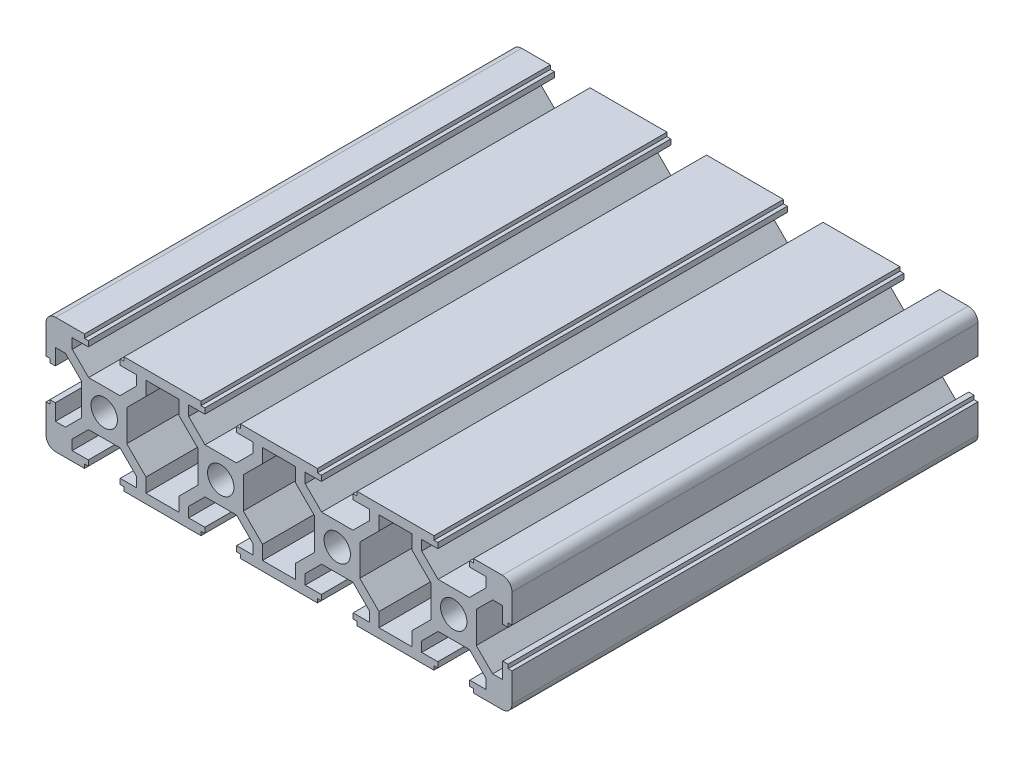
SolidWorks part; units mm, degrees
ref_plane "前视基准面" through (0, 0, 0) normal (0, 0, 1) x (1, 0, 0)
ref_plane "上视基准面" through (0, 0, 0) normal (0, 1, 0) x (1, 0, 0)
ref_plane "右视基准面" through (0, 0, 0) normal (1, 0, 0) x (0, 0, -1)
sketch "草图1" plane through (0, 0, 0) normal (0, 0, 1) x (1, 0, 0)
  line B0 (84.2, -4.0358) -> (84.2, 4.0358)
  line B1 (84.2, 4.0358) -> (79.25, 8.9858)
  line B2 (79.25, 8.9858) -> (79.25, 12.6)
  line B3 (79.25, 12.6) -> (70.75, 12.6)
  line B4 (70.75, 12.6) -> (70.75, 8.9858)
  line B5 (70.75, 8.9858) -> (65.8, 4.0358)
  line B6 (65.8, 4.0358) -> (65.8, -4.0358)
  line B7 (65.8, -4.0358) -> (70.75, -8.9858)
  line B8 (70.75, -8.9858) -> (70.75, -12.6)
  line B9 (70.75, -12.6) -> (79.25, -12.6)
  line B10 (79.25, -12.6) -> (79.25, -8.9858)
  line B11 (79.25, -8.9858) -> (84.2, -4.0358)
  line B12 (54.2, -4.0358) -> (54.2, 4.0358)
  line B13 (54.2, 4.0358) -> (49.25, 8.9858)
  line B14 (49.25, 8.9858) -> (49.25, 12.6)
  line B15 (49.25, 12.6) -> (40.75, 12.6)
  line B16 (40.75, 12.6) -> (40.75, 8.9858)
  line B17 (40.75, 8.9858) -> (35.8, 4.0358)
  line B18 (35.8, 4.0358) -> (35.8, -4.0358)
  line B19 (35.8, -4.0358) -> (40.75, -8.9858)
  line B20 (40.75, -8.9858) -> (40.75, -12.6)
  line B21 (40.75, -12.6) -> (49.25, -12.6)
  line B22 (49.25, -12.6) -> (49.25, -8.9858)
  line B23 (49.25, -8.9858) -> (54.2, -4.0358)
  line B24 (24.2, -4.0358) -> (24.2, 4.0358)
  line B25 (24.2, 4.0358) -> (19.25, 8.9858)
  line B26 (19.25, 8.9858) -> (19.25, 12.6)
  line B27 (19.25, 12.6) -> (10.75, 12.6)
  line B28 (10.75, 12.6) -> (10.75, 8.9858)
  line B29 (10.75, 8.9858) -> (5.8, 4.0358)
  line B30 (5.8, 4.0358) -> (5.8, -4.0358)
  line B31 (5.8, -4.0358) -> (10.75, -8.9858)
  line B32 (10.75, -8.9858) -> (10.75, -12.6)
  line B33 (10.75, -12.6) -> (19.25, -12.6)
  line B34 (19.25, -12.6) -> (19.25, -8.9858)
  line B35 (19.25, -8.9858) -> (24.2, -4.0358)
  line B36 (104, 5.1) -> (105, 5.1)
  line B37 (105, 5.1) -> (105, 12.5)
  line B38 (102.5, 15) -> (95.1, 15)
  line B39 (95.1, 15) -> (95.1, 14)
  line B40 (95.1, 14) -> (94.1, 14)
  line B41 (94.1, 14) -> (94.1, 12.6)
  line B42 (94.1, 12.6) -> (98.25, 12.6)
  line B43 (98.25, 12.6) -> (98.25, 10.0142)
  line B44 (98.25, 10.0142) -> (94.0358, 5.8)
  line B45 (94.0358, 5.8) -> (85.9642, 5.8)
  line B46 (85.9642, 5.8) -> (81.75, 10.0142)
  line B47 (81.75, 10.0142) -> (81.75, 12.6)
  line B48 (81.75, 12.6) -> (85.9, 12.6)
  line B49 (85.9, 12.6) -> (85.9, 14)
  line B50 (85.9, 14) -> (84.9, 14)
  line B51 (84.9, 14) -> (84.9, 15)
  line B52 (84.9, 15) -> (65.1, 15)
  line B53 (65.1, 15) -> (65.1, 14)
  line B54 (65.1, 14) -> (64.1, 14)
  line B55 (64.1, 14) -> (64.1, 12.6)
  line B56 (64.1, 12.6) -> (68.25, 12.6)
  line B57 (68.25, 12.6) -> (68.25, 10.0142)
  line B58 (68.25, 10.0142) -> (64.0358, 5.8)
  line B59 (64.0358, 5.8) -> (55.9642, 5.8)
  line B60 (55.9642, 5.8) -> (51.75, 10.0142)
  line B61 (51.75, 10.0142) -> (51.75, 12.6)
  line B62 (51.75, 12.6) -> (55.9, 12.6)
  line B63 (55.9, 12.6) -> (55.9, 14)
  line B64 (55.9, 14) -> (54.9, 14)
  line B65 (54.9, 14) -> (54.9, 15)
  line B66 (54.9, 15) -> (35.1, 15)
  line B67 (35.1, 15) -> (35.1, 14)
  line B68 (35.1, 14) -> (34.1, 14)
  line B69 (34.1, 14) -> (34.1, 12.6)
  line B70 (34.1, 12.6) -> (38.25, 12.6)
  line B71 (38.25, 12.6) -> (38.25, 10.0142)
  line B72 (38.25, 10.0142) -> (34.0358, 5.8)
  line B73 (34.0358, 5.8) -> (25.9642, 5.8)
  line B74 (25.9642, 5.8) -> (21.75, 10.0142)
  line B75 (21.75, 10.0142) -> (21.75, 12.6)
  line B76 (21.75, 12.6) -> (25.9, 12.6)
  line B77 (25.9, 12.6) -> (25.9, 14)
  line B78 (25.9, 14) -> (24.9, 14)
  line B79 (24.9, 14) -> (24.9, 15)
  line B80 (24.9, 15) -> (5.1, 15)
  line B81 (5.1, 15) -> (5.1, 14)
  line B82 (5.1, 14) -> (4.1, 14)
  line B83 (4.1, 14) -> (4.1, 12.6)
  line B84 (4.1, 12.6) -> (8.25, 12.6)
  line B85 (8.25, 12.6) -> (8.25, 10.0142)
  line B86 (8.25, 10.0142) -> (4.0358, 5.8)
  line B87 (4.0358, 5.8) -> (-4.0358, 5.8)
  line B88 (-4.0358, 5.8) -> (-8.25, 10.0142)
  line B89 (-8.25, 10.0142) -> (-8.25, 12.6)
  line B90 (-8.25, 12.6) -> (-4.1, 12.6)
  line B91 (-4.1, 12.6) -> (-4.1, 14)
  line B92 (-4.1, 14) -> (-5.1, 14)
  line B93 (-5.1, 14) -> (-5.1, 15)
  line B94 (-5.1, 15) -> (-12.5, 15)
  line B95 (-15, 12.5) -> (-15, 5.1)
  line B96 (-15, 5.1) -> (-14, 5.1)
  line B97 (-14, 5.1) -> (-14, 4.1)
  line B98 (-14, 4.1) -> (-12.6, 4.1)
  line B99 (-12.6, 4.1) -> (-12.6, 8.25)
  line B100 (-12.6, 8.25) -> (-10.0142, 8.25)
  line B101 (-10.0142, 8.25) -> (-5.8, 4.0358)
  line B102 (-5.8, 4.0358) -> (-5.8, -4.0358)
  line B103 (-5.8, -4.0358) -> (-10.0142, -8.25)
  line B104 (-10.0142, -8.25) -> (-12.6, -8.25)
  line B105 (-12.6, -8.25) -> (-12.6, -4.1)
  line B106 (-12.6, -4.1) -> (-14, -4.1)
  line B107 (-14, -4.1) -> (-14, -5.1)
  line B108 (-14, -5.1) -> (-15, -5.1)
  line B109 (-15, -5.1) -> (-15, -12.5)
  line B110 (-12.5, -15) -> (-5.1, -15)
  line B111 (-5.1, -15) -> (-5.1, -14)
  line B112 (-5.1, -14) -> (-4.1, -14)
  line B113 (-4.1, -14) -> (-4.1, -12.6)
  line B114 (-4.1, -12.6) -> (-8.25, -12.6)
  line B115 (-8.25, -12.6) -> (-8.25, -10.0142)
  line B116 (-8.25, -10.0142) -> (-4.0358, -5.8)
  line B117 (-4.0358, -5.8) -> (4.0358, -5.8)
  line B118 (4.0358, -5.8) -> (8.25, -10.0142)
  line B119 (8.25, -10.0142) -> (8.25, -12.6)
  line B120 (8.25, -12.6) -> (4.1, -12.6)
  line B121 (4.1, -12.6) -> (4.1, -14)
  line B122 (4.1, -14) -> (5.1, -14)
  line B123 (5.1, -14) -> (5.1, -15)
  line B124 (5.1, -15) -> (24.9, -15)
  line B125 (24.9, -15) -> (24.9, -14)
  line B126 (24.9, -14) -> (25.9, -14)
  line B127 (25.9, -14) -> (25.9, -12.6)
  line B128 (25.9, -12.6) -> (21.75, -12.6)
  line B129 (21.75, -12.6) -> (21.75, -10.0142)
  line B130 (21.75, -10.0142) -> (25.9642, -5.8)
  line B131 (25.9642, -5.8) -> (34.0358, -5.8)
  line B132 (34.0358, -5.8) -> (38.25, -10.0142)
  line B133 (38.25, -10.0142) -> (38.25, -12.6)
  line B134 (38.25, -12.6) -> (34.1, -12.6)
  line B135 (34.1, -12.6) -> (34.1, -14)
  line B136 (34.1, -14) -> (35.1, -14)
  line B137 (35.1, -14) -> (35.1, -15)
  line B138 (35.1, -15) -> (54.9, -15)
  line B139 (54.9, -15) -> (54.9, -14)
  line B140 (54.9, -14) -> (55.9, -14)
  line B141 (55.9, -14) -> (55.9, -12.6)
  line B142 (55.9, -12.6) -> (51.75, -12.6)
  line B143 (51.75, -12.6) -> (51.75, -10.0142)
  line B144 (51.75, -10.0142) -> (55.9642, -5.8)
  line B145 (55.9642, -5.8) -> (64.0358, -5.8)
  line B146 (64.0358, -5.8) -> (68.25, -10.0142)
  line B147 (68.25, -10.0142) -> (68.25, -12.6)
  line B148 (68.25, -12.6) -> (64.1, -12.6)
  line B149 (64.1, -12.6) -> (64.1, -14)
  line B150 (64.1, -14) -> (65.1, -14)
  line B151 (65.1, -14) -> (65.1, -15)
  line B152 (65.1, -15) -> (84.9, -15)
  line B153 (84.9, -15) -> (84.9, -14)
  line B154 (84.9, -14) -> (85.9, -14)
  line B155 (85.9, -14) -> (85.9, -12.6)
  line B156 (85.9, -12.6) -> (81.75, -12.6)
  line B157 (81.75, -12.6) -> (81.75, -10.0142)
  line B158 (81.75, -10.0142) -> (85.9642, -5.8)
  line B159 (85.9642, -5.8) -> (94.0358, -5.8)
  line B160 (94.0358, -5.8) -> (98.25, -10.0142)
  line B161 (98.25, -10.0142) -> (98.25, -12.6)
  line B162 (98.25, -12.6) -> (94.1, -12.6)
  line B163 (94.1, -12.6) -> (94.1, -14)
  line B164 (94.1, -14) -> (95.1, -14)
  line B165 (95.1, -14) -> (95.1, -15)
  line B166 (95.1, -15) -> (102.5, -15)
  line B167 (105, -12.5) -> (105, -5.1)
  line B168 (105, -5.1) -> (104, -5.1)
  line B169 (104, -5.1) -> (104, -4.1)
  line B170 (104, -4.1) -> (102.6, -4.1)
  line B171 (102.6, -4.1) -> (102.6, -8.25)
  line B172 (102.6, -8.25) -> (100.0142, -8.25)
  line B173 (100.0142, -8.25) -> (95.8, -4.0358)
  line B174 (95.8, -4.0358) -> (95.8, 4.0358)
  line B175 (95.8, 4.0358) -> (100.0142, 8.25)
  line B176 (100.0142, 8.25) -> (102.6, 8.25)
  line B177 (102.6, 8.25) -> (102.6, 4.1)
  line B178 (102.6, 4.1) -> (104, 4.1)
  line B179 (104, 4.1) -> (104, 5.1)
  arc B180 (105, 12.5) -> (102.5, 15) centre (102.5, 12.5) ccw
  arc B181 (-12.5, 15) -> (-15, 12.5) centre (-12.5, 12.5) ccw
  arc B182 (-15, -12.5) -> (-12.5, -15) centre (-12.5, -12.5) ccw
  arc B183 (102.5, -15) -> (105, -12.5) centre (102.5, -12.5) ccw
  circle B184 centre (90, 0) radius 3.4
  circle B185 centre (60, 0) radius 3.4
  circle B186 centre (30, 0) radius 3.4
  circle B187 centre (0, 0) radius 3.4
sketch_block_instance "A$C32D42BE7-1"
sketch_block "A$C32D42BE7"
extrude "凸台-拉伸1" add sketch "草图1" along normal blind 120
